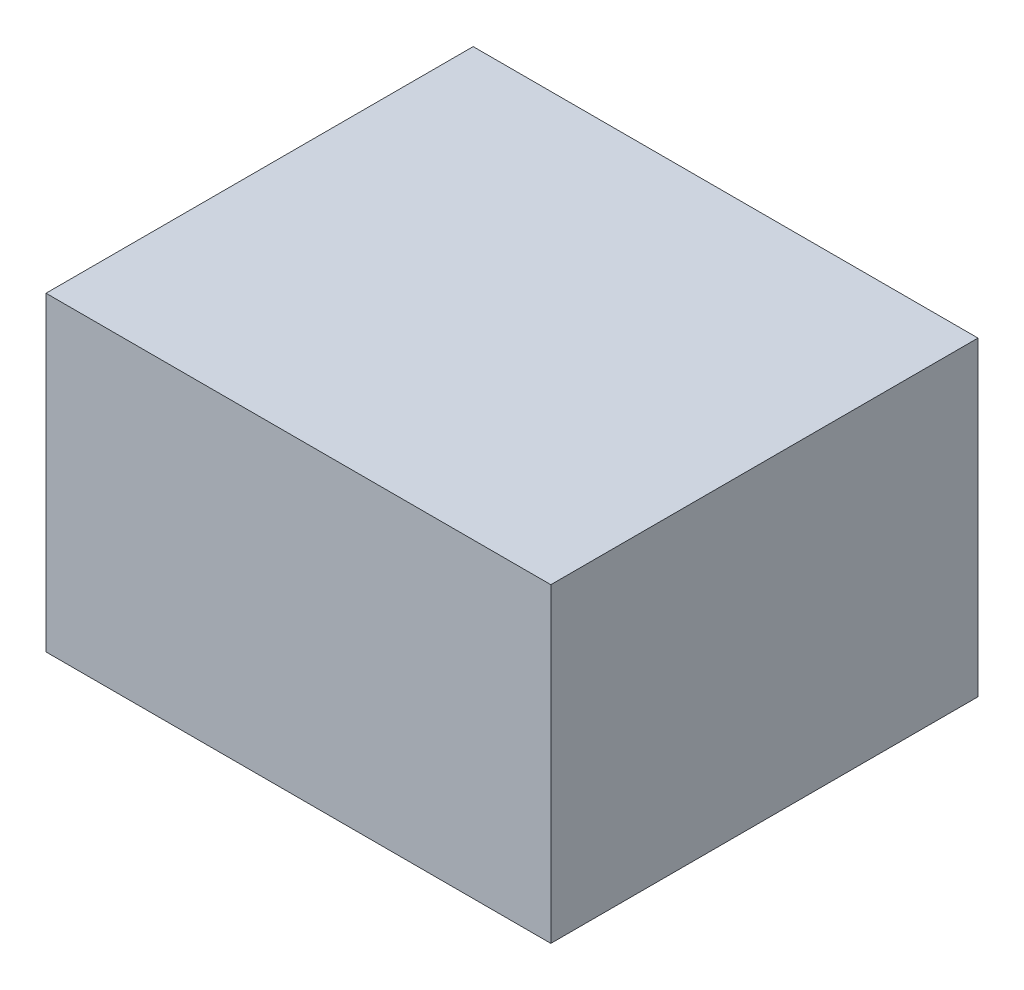
SolidWorks part; units mm, degrees
ref_plane "前视基准面" through (0, 0, 0) normal (0, 0, 1) x (1, 0, 0)
ref_plane "上视基准面" through (0, 0, 0) normal (0, 1, 0) x (1, 0, 0)
ref_plane "右视基准面" through (0, 0, 0) normal (1, 0, 0) x (0, 0, -1)
sketch "草图1" plane through (0, 0, 0) normal (0, 1, 0) x (1, 0, 0)
  line L1 (-32.5, -27.5) -> (32.5, -27.5)
  line L2 (-32.5, -27.5) -> (-32.5, 27.5)
  line L3 (-32.5, 27.5) -> (32.5, 27.5)
  line L4 (32.5, -27.5) -> (32.5, 27.5)
  line L5 (-32.5, -27.5) -> (32.5, 27.5) construction
  line L6 (-32.5, 27.5) -> (32.5, -27.5) construction
  point P0 (0, 0)
  dimension "D1" = 65
  dimension "D2" = 55
extrude "凸台-拉伸1" add sketch "草图1" along normal blind 40
